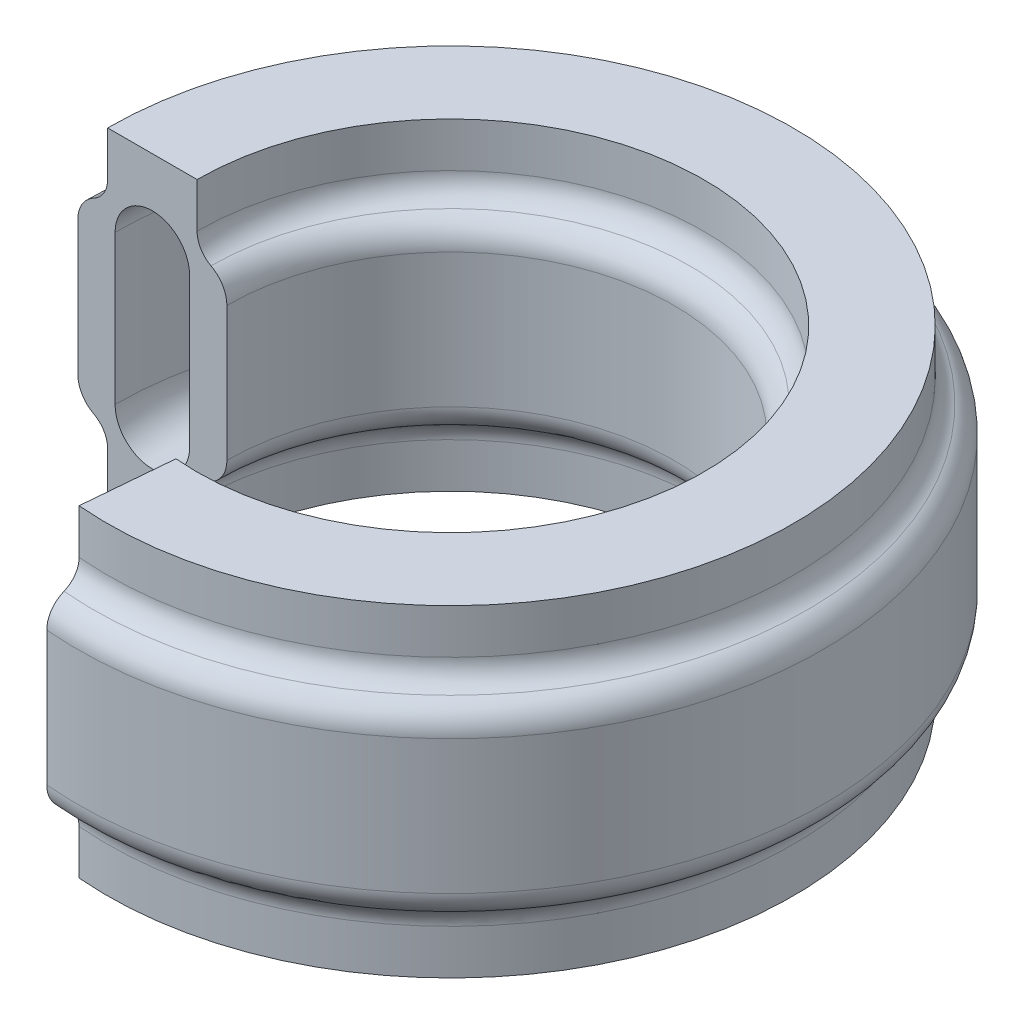
SolidWorks part; units mm, degrees
ref_plane "Front Plane" through (0, 0, 0) normal (0, 0, 1) x (1, 0, 0)
ref_plane "Top Plane" through (0, 0, 0) normal (0, 1, 0) x (1, 0, 0)
ref_plane "Right Plane" through (0, 0, 0) normal (1, 0, 0) x (0, 0, -1)
sketch "Sketch1" plane through (0, 0, 0) normal (0, 0, 1) x (1, 0, 0)
  line L0 (0, 17.6891) -> (0, -14.7177) construction
  line L1 (-20, 11.1644) -> (-20, -10.4688) construction
  line L2 (-22.5, 5.3478) -> (-22.5, -4.6522)
  line L3 (-17, 11.1644) -> (-23, 11.1644)
  line L5 (-17, -10.4688) -> (-23, -10.4688)
  line L6 (-23, -10.4688) -> (-23, -7.4688)
  line L7 (-23, 11.1644) -> (-23, 8.1644)
  line L8 (-25, 4.8478) -> (-25, -4.1522)
  line L10 (-17.5, 5.3478) -> (-17.5, -4.6522)
  line L11 (-17, -10.4688) -> (-17, -7.4688)
  line L12 (-15, 4.8478) -> (-15, -4.1522)
  line L13 (-17, 11.1644) -> (-17, 8.1644)
  arc A0 (-23.9333, 6.6167) -> (-25, 4.8478) centre (-23, 4.8478) ccw
  arc A1 (-25, -4.1522) -> (-23.9333, -5.9211) centre (-23, -4.1522) ccw
  arc A2 (-23, -7.4688) -> (-23.9333, -5.9211) centre (-24.75, -7.4688) ccw
  arc A3 (-23, 8.1644) -> (-23.9333, 6.6167) centre (-24.75, 8.1644) cw
  arc A4 (-17.5, 5.3478) -> (-22.5, 5.3478) centre (-20, 5.3478) ccw
  arc A5 (-17.5, -4.6522) -> (-22.5, -4.6522) centre (-20, -4.6522) cw
  arc A6 (-17, -7.4688) -> (-16.0667, -5.9211) centre (-15.25, -7.4688) cw
  arc A7 (-15, -4.1522) -> (-16.0667, -5.9211) centre (-17, -4.1522) cw
  arc A8 (-16.0667, 6.6167) -> (-15, 4.8478) centre (-17, 4.8478) cw
  arc A9 (-17, 8.1644) -> (-16.0667, 6.6167) centre (-15.25, 8.1644) ccw
  point P3 (-25, 0.3478)
  point P22 (-22.5, 0.3478)
  point P26 (-17.5, 0.3478)
  point P27 (-15, 0.3478)
  dimension "D2" = 1.75
  dimension "D1" = 2
  dimension "D4" = 9
  dimension "D6" = 5
  dimension "D8" = 20
  dimension "D3" = 3
  dimension "D5" = 3
  dimension "D7" = 10
revolve "Revolve1" add sketch "Sketch1" angle 275 about L0
